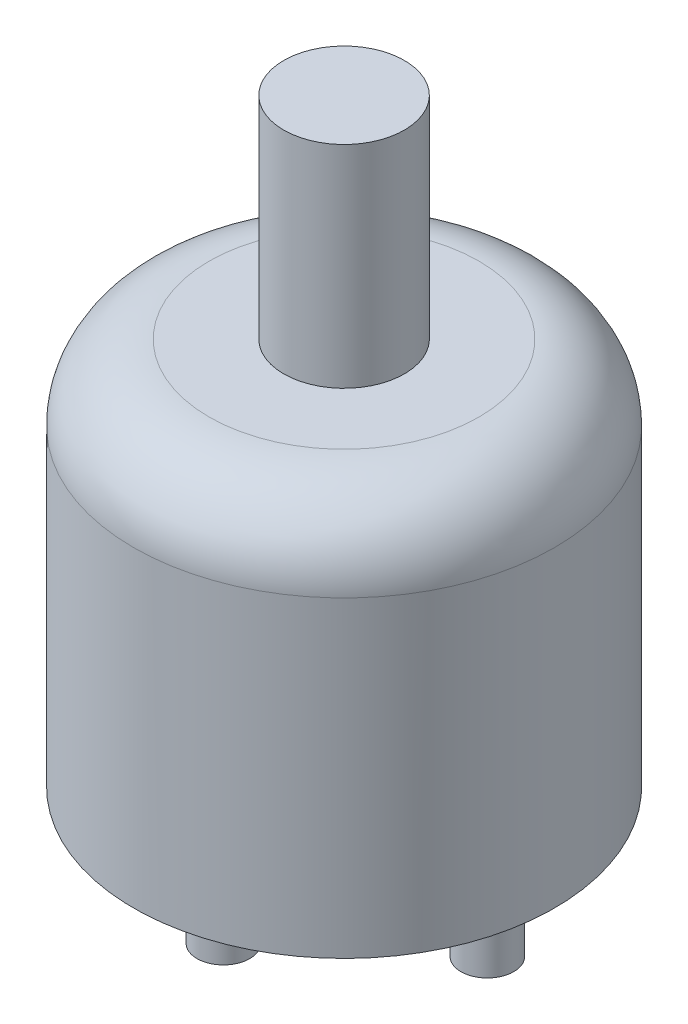
SolidWorks part; units mm, degrees
ref_plane "Front Plane" through (0, 0, 0) normal (0, 0, 1) x (1, 0, 0)
ref_plane "Top Plane" through (0, 0, 0) normal (0, 1, 0) x (1, 0, 0)
ref_plane "Right Plane" through (0, 0, 0) normal (1, 0, 0) x (0, 0, -1)
sketch "Sketch1" plane through (0, 0, 0) normal (0, 1, 0) x (1, 0, 0)
  circle A0 centre (0, 0) radius 13.95
  dimension "D1" = 27.9
extrude "Boss-Extrude1" add sketch "Sketch1" along normal blind 25.7
fillet "Fillet1" radius 5 1 edges at (0, 25.7, 13.95)
sketch "Sketch2" plane through (0, 25.7, 0) normal (0, 1, 0) x (1, 0, 0)
  circle A0 centre (0, 0) radius 4
  dimension "D1" = 8
extrude "Boss-Extrude2" add sketch "Sketch2" along normal blind 14
sketch "Sketch3" plane through (0, 0, 0) normal (0, -1, 0) x (1, 0, 0)
  line L0 (13.95, 0) -> (-13.95, 0)
  line L1 (0, 13.95) -> (0, -13.95)
  circle A0 centre (0, 0) radius 13.95 construction
  circle A1 centre (0, 8) radius 1.75
  circle A2 centre (9.5, 0) radius 1.75
  circle A3 centre (0, -8) radius 1.75
  circle A4 centre (-9.5, 0) radius 1.75
  dimension "D1" = 3.5
  dimension "D2" = 3.5
  dimension "D3" = 3.5
  dimension "D4" = 3.5
  dimension "D5" = 8
  dimension "D6" = 8
  dimension "D7" = 9.5
  dimension "D8" = 9.5
extrude "Boss-Extrude3" add sketch "Sketch3" along normal blind 5 contours L1 A1 | L1 A1 | L0 A4 | L0 A4 | L1 A3 | L0 A2 | L0 A2
